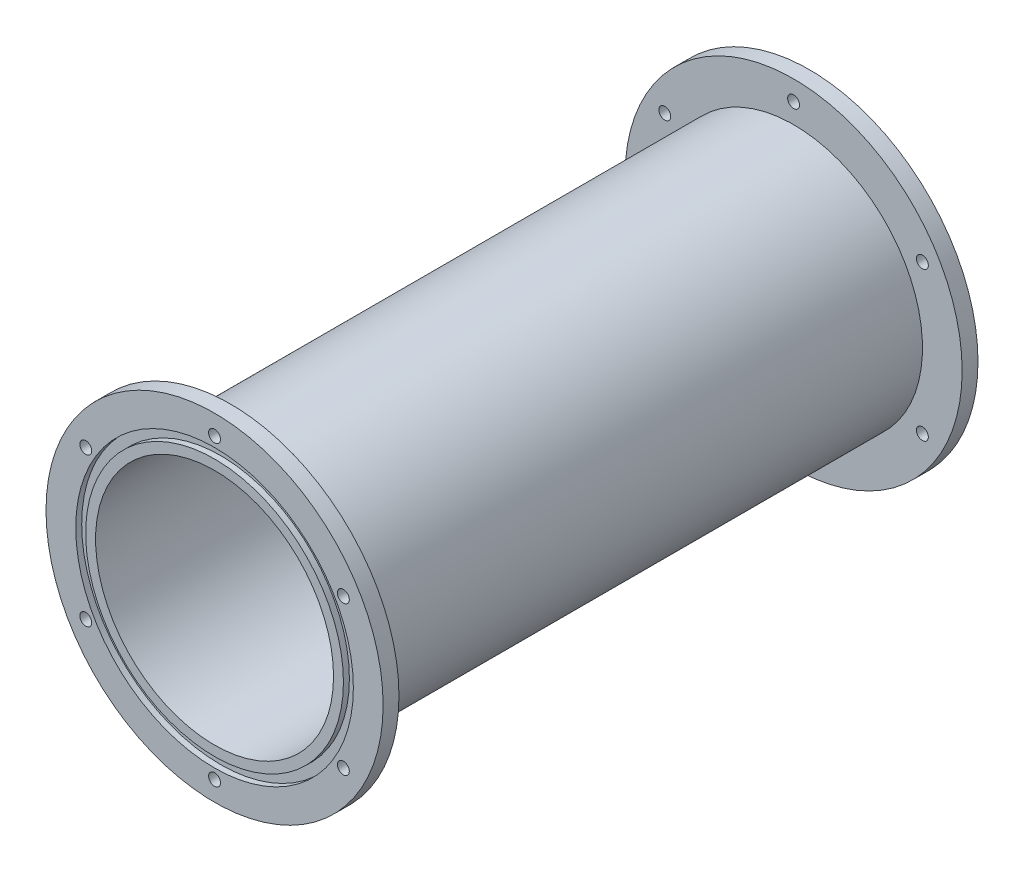
SolidWorks part; units mm, degrees
material "PMMA"
ref_plane "前视基准面" through (0, 0, 0) normal (0, 0, 1) x (1, 0, 0)
ref_plane "上视基准面" through (0, 0, 0) normal (0, 1, 0) x (1, 0, 0)
ref_plane "右视基准面" through (0, 0, 0) normal (1, 0, 0) x (0, 0, -1)
sketch "草图1" plane through (0, 0, 0) normal (0, 0, 1) x (1, 0, 0)
  circle A0 centre (0, 0) radius 65
  circle A1 centre (0, 0) radius 60
  dimension "D1" = 130
  dimension "D2" = 120
extrude "凸台-拉伸1" add sketch "草图1" along normal mid plane 300
sketch "草图2" plane through (0, 0, 150) normal (0, 0, 1) x (1, 0, 0)
  circle A0 centre (0, 0) radius 85
  circle A1 centre (0, 0) radius 75 construction
  circle A2 centre (0, 75) radius 3
  circle A3 centre (64.9519, 37.5) radius 3
  circle A4 centre (64.9519, -37.5) radius 3
  circle A5 centre (0, -75) radius 3
  circle A6 centre (-64.9519, -37.5) radius 3
  circle A7 centre (-64.9519, 37.5) radius 3
  circle A8 centre (0, 0) radius 65 construction
  circle A9 centre (0, 0) radius 65
  point P18 (0, 0)
  dimension "D1" = 170
  dimension "D2" = 150
  dimension "D3" = 6
  dimension "D4" = 6
extrude "凸台-拉伸2" add sketch "草图2" against normal blind 8
sketch "草图3" plane through (0, 0, 150) normal (0, 0, 1) x (1, 0, 0)
  circle A0 centre (0, 0) radius 65
  circle A1 centre (0, 0) radius 70
  dimension "D1" = 130
  dimension "D2" = 140
extrude "切除-拉伸1" cut sketch "草图3" against normal blind 3
mirror "镜向1" about plane through (0, 0, 0) normal (0, 0, 1) of "切除-拉伸1", "凸台-拉伸2"
sketch "草图4" plane through (0, 0, 0) normal (0, 0, 1) x (1, 0, 0)
  circle A0 centre (0, 0) radius 75
